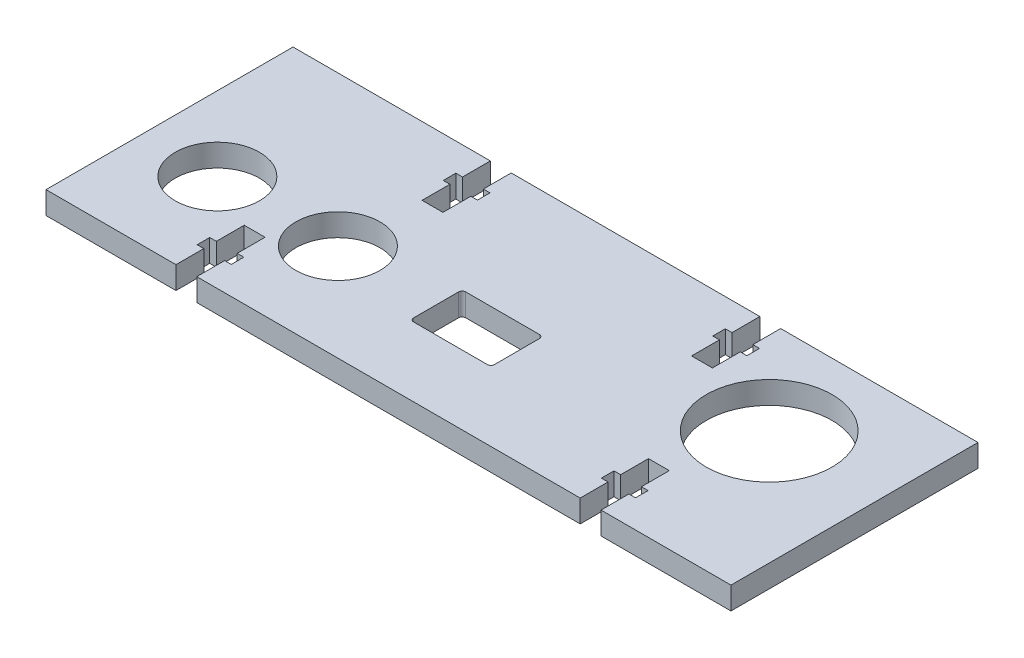
SolidWorks part; units mm, degrees
material "Acrylic (Medium-high impact)"
ref_plane "Front Plane" through (0, 0, 0) normal (0, 0, 1) x (1, 0, 0)
ref_plane "Top Plane" through (0, 0, 0) normal (0, 1, 0) x (1, 0, 0)
ref_plane "Right Plane" through (0, 0, 0) normal (1, 0, 0) x (0, 0, -1)
sketch "Sketch1" plane through (0, 0, 0) normal (0, 1, 0) x (1, 0, 0)
  line L1 (-48.4187, -17.4625) -> (48.4188, -17.4625)
  line L2 (-48.4187, -17.4625) -> (-48.4187, 17.4625)
  line L3 (-48.4187, 17.4625) -> (48.4188, 17.4625)
  line L4 (48.4188, -17.4625) -> (48.4188, 17.4625)
  line L5 (-48.4187, -17.4625) -> (48.4188, 17.4625) construction
  line L6 (-48.4187, 17.4625) -> (48.4188, -17.4625) construction
  point P0 (0, 0)
  dimension "D1" = 96.8375
  dimension "D2" = 34.925
extrude "Boss-Extrude1" add sketch "Sketch1" along normal blind 3.175
hole_wizard "Tap Drill for #0-80 Tap1" [suppressed] positions "Sketch2" profile "Sketch3" hole size "#0-80" standard "ANSI Inch"
sketch "Sketch2" plane through (0, 3.175, 0) normal (0, 1, 0) x (1, 0, 0)
  point P20 (40.9766, -0.9208)
  point P22 (23.4887, -0.9208)
  point P24 (32.2326, 13.4048)
sketch "Sketch3" plane through (40.9766, 3.175, 0.9208) normal (1, 0, 0) x (0, 0, 1)
  line L0 (0, 0) -> (0, 3.175)
  line L1 (0, 3.175) -> (0.5956, 3.175)
  line L2 (0.5956, 3.175) -> (0.5956, 0)
  line L5 (0.5956, 0) -> (0, 0)
  line L11 (0, -6.35) -> (0, 107.95) construction
  dimension "Thru Hole Dia." = 1.1913
  dimension "Thru Hole Depth" = 3.175
hole_wizard "7/16 Clearance Hole1" positions "Sketch4" profile "Sketch5" hole size "7/16" standard "ANSI Inch" end condition through all
sketch "Sketch4" plane through (0, 3.175, 0) normal (0, 1, 0) x (1, 0, 0)
  point P13 (-37.9095, -3.7465)
  point P14 (-20.8661, -3.7465)
sketch "Sketch5" plane through (-37.9095, 3.175, 3.7465) normal (1, 0, 0) x (0, 0, 1)
  line L0 (0, 0) -> (0, 3.175)
  line L1 (0, 3.175) -> (5.9525, 3.175)
  line L2 (5.9525, 3.175) -> (5.9525, 0)
  line L5 (5.9525, 0) -> (0, 0)
  line L11 (0, -6.35) -> (0, 107.95) construction
  dimension "Thru Hole Dia." = 11.905
  dimension "Thru Hole Depth" = 3.175
sketch "Sketch6" plane through (0, 3.175, 0) normal (0, 1, 0) x (1, 0, 0)
  line L0 (4.699, -7.6835) -> (-6.731, -7.6835)
  line L1 (3.429, -6.4135) -> (-5.461, -6.4135) construction
  line L2 (3.429, -6.4135) -> (3.429, -1.5875) construction
  line L3 (3.429, -1.5875) -> (-5.461, -1.5875) construction
  line L4 (-5.461, -6.4135) -> (-5.461, -1.5875) construction
  line L5 (-6.731, -7.6835) -> (-6.731, -0.3175)
  line L6 (4.699, -0.3175) -> (-6.731, -0.3175)
  line L7 (4.699, -7.6835) -> (4.699, -0.3175)
  dimension "D1" = 1.27
extrude "Cut-Extrude1" cut sketch "Sketch6" against normal through all
sketch "Sketch7" plane through (0, 3.175, 0) normal (0, 1, 0) x (1, 0, 0)
  line L0 (48.4188, -17.4625) -> (48.4188, 17.4625) construction
  line L1 (48.4188, -12.5857) -> (42.9578, -12.5857)
  line L2 (48.4188, -12.5857) -> (48.4188, -9.6393)
  line L3 (48.4188, -9.6393) -> (42.9578, -9.6393)
  line L4 (35.7188, -12.5857) -> (35.7188, -9.6393)
  line L5 (48.4188, -12.5857) -> (35.7188, -9.6393) construction
  line L6 (48.4188, -11.1125) -> (35.7188, -11.1125) construction
  line L7 (-48.4187, -17.4625) -> (48.4188, -17.4625) construction
  line L8 (48.4188, 9.6393) -> (42.9578, 9.6393)
  line L9 (42.9578, -8.6995) -> (41.1798, -8.6995)
  line L10 (42.9578, -8.6995) -> (42.9578, -9.6393)
  line L11 (42.9578, -13.5255) -> (41.1798, -13.5255)
  line L12 (41.1798, -8.6995) -> (41.1798, -9.6393)
  line L13 (42.9578, -8.6995) -> (41.1798, -13.5255) construction
  line L14 (42.9578, -13.5255) -> (41.1798, -8.6995) construction
  line L15 (42.9578, -12.5857) -> (42.9578, -13.5255)
  line L16 (41.1798, -9.6393) -> (35.7188, -9.6393)
  line L17 (41.1798, -12.5857) -> (41.1798, -13.5255)
  line L18 (41.1798, -12.5857) -> (35.7188, -12.5857)
  line L19 (48.4188, 9.6393) -> (48.4188, 12.5857)
  line L20 (48.4188, 12.5857) -> (42.9578, 12.5857)
  line L21 (35.7188, 9.6393) -> (35.7188, 12.5857)
  line L22 (42.9578, 13.5255) -> (41.1798, 13.5255)
  line L23 (42.9578, 13.5255) -> (42.9578, 12.5857)
  line L24 (42.9578, 8.6995) -> (41.1798, 8.6995)
  line L25 (41.1798, 13.5255) -> (41.1798, 12.5857)
  line L26 (42.9578, 9.6393) -> (42.9578, 8.6995)
  line L27 (41.1798, 12.5857) -> (35.7188, 12.5857)
  line L28 (41.1798, 9.6393) -> (41.1798, 8.6995)
  line L29 (41.1798, 9.6393) -> (35.7188, 9.6393)
  line L30 (48.4188, 9.6393) -> (35.7188, 12.5857) construction
  line L31 (48.4188, 11.1125) -> (35.7188, 11.1125) construction
  line L32 (42.9578, 13.5255) -> (41.1798, 8.6995) construction
  line L33 (42.9578, 8.6995) -> (41.1798, 13.5255) construction
  line L34 (0, 0) -> (0, 17.4625) construction
  line L35 (48.4188, 17.4625) -> (-48.4187, 17.4625) construction
  line L36 (-42.9578, 8.6995) -> (-41.1798, 13.5255) construction
  line L37 (-42.9578, 13.5255) -> (-41.1798, 8.6995) construction
  line L38 (-48.4188, 11.1125) -> (-35.7188, 11.1125) construction
  line L39 (-48.4188, 9.6393) -> (-35.7188, 12.5857) construction
  line L40 (-42.9578, -13.5255) -> (-41.1798, -8.6995) construction
  line L41 (-42.9578, -8.6995) -> (-41.1798, -13.5255) construction
  line L42 (-48.4188, -11.1125) -> (-35.7188, -11.1125) construction
  line L43 (-48.4188, -12.5857) -> (-35.7188, -9.6393) construction
  line L44 (-41.1798, 9.6393) -> (-35.7188, 9.6393)
  line L45 (-41.1798, 9.6393) -> (-41.1798, 8.6995)
  line L46 (-41.1798, 12.5857) -> (-35.7188, 12.5857)
  line L47 (-42.9578, 9.6393) -> (-42.9578, 8.6995)
  line L48 (-41.1798, 13.5255) -> (-41.1798, 12.5857)
  line L49 (-42.9578, 8.6995) -> (-41.1798, 8.6995)
  line L50 (-42.9578, 13.5255) -> (-42.9578, 12.5857)
  line L51 (-42.9578, 13.5255) -> (-41.1798, 13.5255)
  line L52 (-35.7188, 9.6393) -> (-35.7188, 12.5857)
  line L53 (-48.4188, 12.5857) -> (-42.9578, 12.5857)
  line L54 (-48.4188, 9.6393) -> (-48.4188, 12.5857)
  line L55 (-41.1798, -12.5857) -> (-35.7188, -12.5857)
  line L56 (-41.1798, -12.5857) -> (-41.1798, -13.5255)
  line L57 (-41.1798, -9.6393) -> (-35.7188, -9.6393)
  line L58 (-42.9578, -12.5857) -> (-42.9578, -13.5255)
  line L59 (-41.1798, -8.6995) -> (-41.1798, -9.6393)
  line L60 (-42.9578, -13.5255) -> (-41.1798, -13.5255)
  line L61 (-42.9578, -8.6995) -> (-42.9578, -9.6393)
  line L62 (-42.9578, -8.6995) -> (-41.1798, -8.6995)
  line L63 (-48.4188, 9.6393) -> (-42.9578, 9.6393)
  line L64 (-35.7188, -12.5857) -> (-35.7188, -9.6393)
  line L65 (-48.4188, -9.6393) -> (-42.9578, -9.6393)
  line L66 (-48.4188, -12.5857) -> (-48.4188, -9.6393)
  line L67 (-48.4188, -12.5857) -> (-42.9578, -12.5857)
  point P10 (42.0688, -11.1125)
  point P26 (42.0688, 11.1125)
  point P67 (-42.0688, 11.1125)
  point P68 (-42.0688, -11.1125)
  dimension "D1" = 6.35
  dimension "D2" = 2.9464
  dimension "D3" = 12.7
  dimension "D4" = 1.778
  dimension "D5" = 4.826
  dimension "D6" = 2
extrude "Cut-Extrude2" [suppressed] cut sketch "Sketch7" against normal through all
sketch "Sketch8" plane through (0, 3.175, 0) normal (0, 1, 0) x (1, 0, 0)
  line L0 (-48.4187, -17.4625) -> (48.4188, -17.4625) construction
  line L1 (27.1018, -17.4625) -> (30.0482, -17.4625)
  line L2 (27.1018, -17.4625) -> (27.1018, -13.5255)
  line L3 (27.1018, -7.8105) -> (30.0482, -7.8105)
  line L4 (30.0482, -17.4625) -> (30.0482, -13.5255)
  line L5 (28.575, -17.4625) -> (28.575, -7.8105) construction
  line L6 (27.1018, -13.5255) -> (26.162, -13.5255)
  line L7 (30.988, -11.7475) -> (30.0482, -11.7475)
  line L8 (30.988, -11.7475) -> (30.988, -13.5255)
  line L9 (30.988, -13.5255) -> (30.0482, -13.5255)
  line L10 (26.162, -11.7475) -> (26.162, -13.5255)
  line L11 (30.988, -11.7475) -> (26.162, -13.5255) construction
  line L12 (30.988, -13.5255) -> (26.162, -11.7475) construction
  line L13 (30.0482, -11.7475) -> (30.0482, -7.8105)
  line L14 (27.1018, -11.7475) -> (26.162, -11.7475)
  line L15 (27.1018, -11.7475) -> (27.1018, -7.8105)
  line L16 (-30.0482, -17.4625) -> (-27.1018, -17.4625)
  line L17 (-30.0482, -17.4625) -> (-30.0482, -13.5255)
  line L18 (-30.0482, -7.8105) -> (-27.1018, -7.8105)
  line L19 (-27.1018, -17.4625) -> (-27.1018, -13.5255)
  line L20 (-30.0482, -13.5255) -> (-30.988, -13.5255)
  line L21 (-26.162, -11.7475) -> (-27.1018, -11.7475)
  line L22 (-26.162, -11.7475) -> (-26.162, -13.5255)
  line L23 (-26.162, -13.5255) -> (-27.1018, -13.5255)
  line L24 (-30.988, -11.7475) -> (-30.988, -13.5255)
  line L25 (-27.1018, -11.7475) -> (-27.1018, -7.8105)
  line L26 (-30.0482, -11.7475) -> (-30.988, -11.7475)
  line L27 (-30.0482, -11.7475) -> (-30.0482, -7.8105)
  line L28 (-28.575, -17.4625) -> (-28.575, -7.8105) construction
  line L29 (-26.162, -11.7475) -> (-30.988, -13.5255) construction
  line L30 (-26.162, -13.5255) -> (-30.988, -11.7475) construction
  line L31 (0, 0) -> (-7.905, 0) construction
  line L32 (-26.162, 13.5255) -> (-30.988, 11.7475) construction
  line L33 (-26.162, 11.7475) -> (-30.988, 13.5255) construction
  line L34 (-28.575, 17.4625) -> (-28.575, 7.8105) construction
  line L35 (30.988, 13.5255) -> (26.162, 11.7475) construction
  line L36 (30.988, 11.7475) -> (26.162, 13.5255) construction
  line L37 (28.575, 17.4625) -> (28.575, 7.8105) construction
  line L38 (-30.0482, 11.7475) -> (-30.0482, 7.8105) construction
  line L39 (-30.0482, 11.7475) -> (-30.988, 11.7475) construction
  line L40 (-27.1018, 11.7475) -> (-27.1018, 7.8105) construction
  line L41 (-30.988, 11.7475) -> (-30.988, 13.5255) construction
  line L42 (-26.162, 13.5255) -> (-27.1018, 13.5255) construction
  line L43 (-26.162, 11.7475) -> (-26.162, 13.5255) construction
  line L44 (-26.162, 11.7475) -> (-27.1018, 11.7475) construction
  line L45 (-30.0482, 13.5255) -> (-30.988, 13.5255) construction
  line L46 (-27.1018, 17.4625) -> (-27.1018, 13.5255) construction
  line L47 (-30.0482, 7.8105) -> (-27.1018, 7.8105) construction
  line L48 (-30.0482, 17.4625) -> (-30.0482, 13.5255) construction
  line L49 (-30.0482, 17.4625) -> (-27.1018, 17.4625) construction
  line L50 (27.1018, 11.7475) -> (27.1018, 7.8105) construction
  line L51 (27.1018, 11.7475) -> (26.162, 11.7475) construction
  line L52 (30.0482, 11.7475) -> (30.0482, 7.8105) construction
  line L53 (26.162, 11.7475) -> (26.162, 13.5255) construction
  line L54 (30.988, 13.5255) -> (30.0482, 13.5255) construction
  line L55 (30.988, 11.7475) -> (30.988, 13.5255) construction
  line L56 (30.988, 11.7475) -> (30.0482, 11.7475) construction
  line L57 (27.1018, 13.5255) -> (26.162, 13.5255) construction
  line L58 (30.0482, 17.4625) -> (30.0482, 13.5255) construction
  line L59 (27.1018, 7.8105) -> (30.0482, 7.8105) construction
  line L60 (27.1018, 17.4625) -> (27.1018, 13.5255) construction
  line L61 (27.1018, 17.4625) -> (30.0482, 17.4625) construction
  line L62 (0, 17.4625) -> (0, -17.4625) construction
  line L63 (17.5768, 11.7475) -> (17.5768, 7.8105)
  line L64 (17.5768, 11.7475) -> (16.637, 11.7475)
  line L65 (20.5232, 11.7475) -> (20.5232, 7.8105)
  line L66 (16.637, 11.7475) -> (16.637, 13.5255)
  line L67 (21.463, 13.5255) -> (20.5232, 13.5255)
  line L68 (21.463, 11.7475) -> (21.463, 13.5255)
  line L69 (21.463, 11.7475) -> (20.5232, 11.7475)
  line L70 (17.5768, 13.5255) -> (16.637, 13.5255)
  line L71 (20.5232, 17.4625) -> (20.5232, 13.5255)
  line L72 (17.5768, 7.8105) -> (20.5232, 7.8105)
  line L73 (17.5768, 17.4625) -> (17.5768, 13.5255)
  line L74 (17.5768, 17.4625) -> (20.5232, 17.4625)
  line L75 (21.463, 13.5255) -> (16.637, 11.7475) construction
  line L76 (21.463, 11.7475) -> (16.637, 13.5255) construction
  line L77 (19.05, 17.4625) -> (19.05, 7.8105) construction
  line L78 (-20.5232, 11.7475) -> (-20.5232, 7.8105)
  line L79 (-20.5232, 11.7475) -> (-21.463, 11.7475)
  line L80 (-17.5768, 11.7475) -> (-17.5768, 7.8105)
  line L81 (-21.463, 11.7475) -> (-21.463, 13.5255)
  line L82 (-16.637, 13.5255) -> (-17.5768, 13.5255)
  line L83 (-16.637, 11.7475) -> (-16.637, 13.5255)
  line L84 (-16.637, 11.7475) -> (-17.5768, 11.7475)
  line L85 (-20.5232, 13.5255) -> (-21.463, 13.5255)
  line L86 (-17.5768, 17.4625) -> (-17.5768, 13.5255)
  line L87 (-20.5232, 7.8105) -> (-17.5768, 7.8105)
  line L88 (-20.5232, 17.4625) -> (-20.5232, 13.5255)
  line L89 (-20.5232, 17.4625) -> (-17.5768, 17.4625)
  line L90 (-16.637, 13.5255) -> (-21.463, 11.7475) construction
  line L91 (-16.637, 11.7475) -> (-21.463, 13.5255) construction
  line L92 (-19.05, 17.4625) -> (-19.05, 7.8105) construction
  line L93 (48.4188, 17.4625) -> (-48.4187, 17.4625) construction
  point P8 (28.575, -12.6365)
  point P25 (-28.575, -12.6365)
  point P63 (-28.575, 12.6365)
  point P64 (28.575, 12.6365)
  point P80 (19.05, 12.6365)
  point P95 (-19.05, 12.6365)
  dimension "D1" = 28.575
  dimension "D2" = 9.652
  dimension "D3" = 1.778
  dimension "D4" = 4.826
  dimension "D5" = 2.9464
  dimension "D9" = 19.05
  dimension "D10" = 19.05
  dimension "D11" = 28.575
  dimension "D6" = 2
  dimension "D7" = 2
  dimension "D8" = 2
extrude "Cut-Extrude3" cut sketch "Sketch8" against normal through all
sketch "Sketch9" plane through (0, 3.175, 0) normal (0, 1, 0) x (1, 0, 0)
  circle A0 centre (32.2326, 4.1275) radius 8.89
  dimension "D1" = 17.78
extrude "Cut-Extrude4" cut sketch "Sketch9" against normal through all
fillet "Fillet1" radius 0.508 4 edges at (4.699, 1.5875, 0.3175) (-6.731, 1.5875, 0.3175) (-6.731, 1.5875, 7.6835) (4.699, 1.5875, 7.6835)
equation "\"#4D\"= .116'slot for adding a #4 screw"
equation "\"D5@Sketch8\"=\"#4D\""
equation "\"#4H\"= .38'slot heigth for adding a #4 screw with 1/2\" length"
equation "\"mat\"= 1 / 8'thickness of material"
equation "\"D2@Sketch8\"=\"#4H\""
equation "\"D1@Boss-Extrude1\"=\"mat\""
